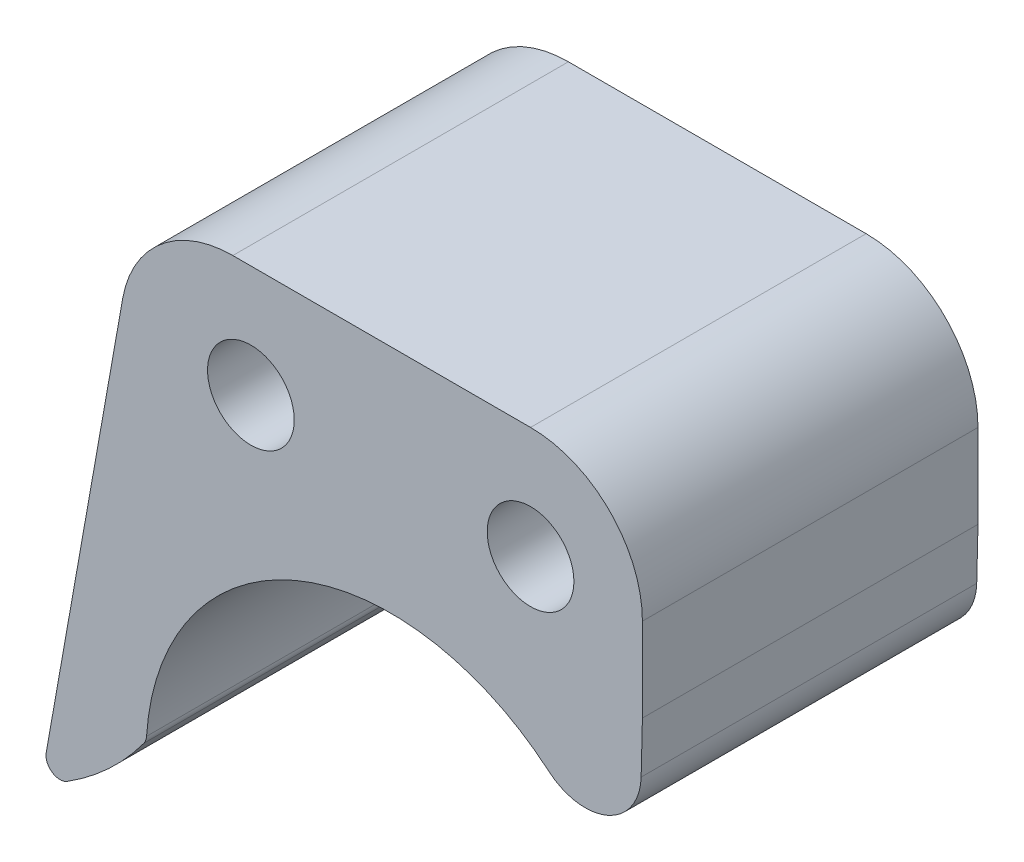
SolidWorks part; units mm, degrees
material "Thornel Mat VMA"
ref_plane "前视基准面" through (0, 0, 0) normal (0, 0, 1) x (1, 0, 0)
ref_plane "上视基准面" through (0, 0, 0) normal (0, 1, 0) x (1, 0, 0)
ref_plane "右视基准面" through (0, 0, 0) normal (1, 0, 0) x (0, 0, -1)
sketch "草图1" plane through (0, 0, 0) normal (0, 0, 1) x (1, 0, 0)
  line L1 (14, -3) -> (-4, -3)
  line L2 (14, -3) -> (14, 4)
  line L3 (14, 4) -> (-4, 4)
  line L4 (-4, -3) -> (-4, 4)
  line L5 (14, -3) -> (-4, 4) construction
  line L6 (14, 4) -> (-4, -3) construction
  circle A0 centre (0, 0) radius 1.55
  circle A1 centre (10, 0) radius 1.55
  point P7 (5, 0.5)
  dimension "D1" = 3.1
  dimension "D6" = 4
  dimension "D2" = 10
  dimension "D3" = 4
  dimension "D4" = 4
  dimension "D5" = 3
extrude "凸台-拉伸1" add sketch "草图1" along normal blind 12
sketch "草图2" plane through (0, 0, 12) normal (0, 0, 1) x (1, 0, 0)
  line L0 (-4, 4) -> (-4, -3)
  line L1 (-4, -3) -> (14, -3) construction
  line L2 (-4, 4) -> (-7.5036, -15.7677)
  line L3 (14, -3) -> (13.7473, -13.2163)
  line L4 (-4, 4) -> (-4, -3) construction
  line L5 (-4, -3) -> (14, -3)
  arc A0 (5.7038, -20.969) -> (-2.9919, -13.3588) centre (5, -13) ccw construction
  arc A2 (5.7038, -20.969) -> (-2.9919, -13.3588) centre (5, -13) ccw construction
  arc A4 (13.7473, -13.2163) -> (-3.7396, -12.5734) centre (5, -13) ccw
  arc A5 (-7.5036, -15.7677) -> (-3.7396, -12.5734) centre (-11.8919, -6.782) ccw
  dimension "D1" = 17.5
  dimension "D3" = 7.5036
extrude "凸台-拉伸2" add sketch "草图2" against normal up to surface (12 mm away) up to face at (5, 0.5, 0)
fillet "圆角1" radius 0.5 2 edges at (-7.5036, -15.7677, 6) (-3.7396, -12.5734, 6)
fillet "圆角2" radius 4 2 edges at (14, 4, 6) (-4, 4, 6)
fillet "圆角3" radius 2 1 edges at (13.7473, -13.2163, 6)
